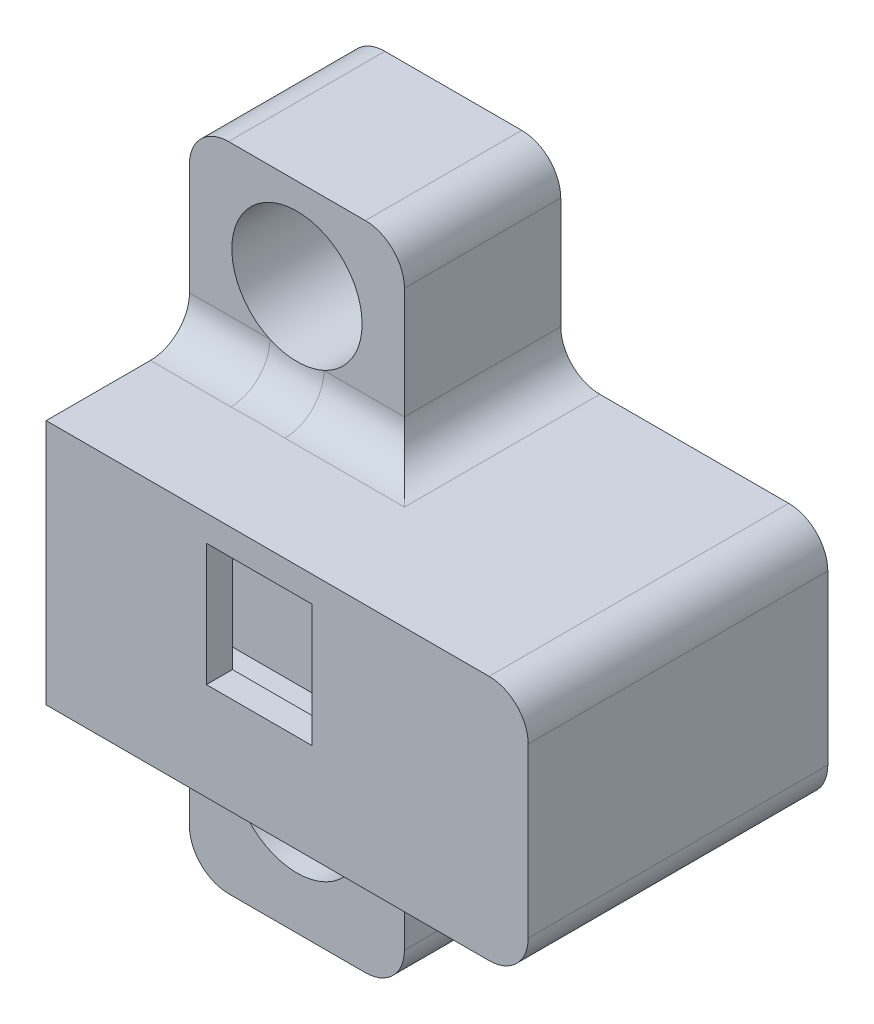
SolidWorks part; units mm, degrees
ref_plane "Alzado" through (0, 0, 0) normal (0, 0, 1) x (1, 0, 0)
ref_plane "Planta" through (0, 0, 0) normal (0, 1, 0) x (1, 0, 0)
ref_plane "Vista lateral" through (0, 0, 0) normal (1, 0, 0) x (0, 0, -1)
sketch "Croquis1" plane through (0, 0, 0) normal (0, 0, 1) x (1, 0, 0)
  line L1 (0, 0) -> (37, 0)
  line L2 (0, 0) -> (0, 18.9)
  line L3 (0, 18.9) -> (37, 18.9)
  line L4 (37, 0) -> (37, 18.9)
  dimension "D1" = 18.9
  dimension "D2" = 37
extrude "Saliente-Extruir1" add sketch "Croquis1" along normal blind 9
shell "Vaciado1" thickness 2
sketch "Croquis2" plane through (0, 0, 0) normal (-1, 0, 0) x (0, 0, 1)
  line L0 (9, 18.9) -> (9, 0) construction
  line L1 (15.4, 3.3) -> (2.6, 3.3)
  line L2 (15.4, 3.3) -> (15.4, 15.6)
  line L3 (15.4, 15.6) -> (2.6, 15.6)
  line L4 (2.6, 3.3) -> (2.6, 15.6)
  line L5 (9, 15.6) -> (9, 3.3) construction
  line L6 (15.4, 9.45) -> (2.6, 9.45) construction
  line L7 (0, 18.9) -> (0, 0) construction
  point P0 (9, 9.45)
  dimension "D1" = 2.6
  dimension "D2" = 12.3
extrude "Cortar-Extruir1" cut sketch "Croquis2" against normal blind 9
sketch "Croquis3" plane through (0, 0, 0) normal (0, 0, -1) x (-1, 0, 0)
  line L0 (-16.5, -16.55) -> (0, -16.55)
  line L1 (-37, 18.9) -> (-16.5, 18.9)
  line L2 (-37, 18.9) -> (-37, 0)
  line L3 (-37, 0) -> (-16.5, 0)
  line L4 (0, 18.9) -> (0, 0)
  line L5 (-16.5, -16.55) -> (-16.5, 0)
  line L6 (0, -16.55) -> (0, 33.45)
  line L7 (-16.5, 33.45) -> (0, 33.45)
  line L8 (-8.25, 33.45) -> (-8.25, -16.55) construction
  line L9 (0, 0) -> (-37, 0) construction
  line L10 (-37, 9.45) -> (0, 9.45) construction
  line L11 (-16.5, 18.9) -> (-16.5, 33.45)
  line L12 (-11.0385, 16.9) -> (-16.5, 33.45) construction
  line L14 (-8.25, 8.45) -> (-5.4615, 16.9) construction
  circle A0 centre (-8.25, 26.45) radius 2.5
  circle A1 centre (-8.25, -7.55) radius 2.5
  point P7 (-8.25, 9.45)
  line M10 (0, 0) -> (0, 18.9)
  line M11 (0, 18.9) -> (-37, 18.9)
  line M12 (-37, 18.9) -> (-37, 0)
  line M13 (-37, 0) -> (0, 0)
  dimension "D3" = 5
  dimension "D1" = 16.5
  dimension "D2" = 50
  dimension "D4" = 7
  dimension "D5" = 0
extrude "Saliente-Extruir2" add sketch "Croquis3" along normal blind 12 contours L11 L6 L7 M11 | L0 L6 L5 M13 | M13 M10 M11 M12
sketch "Croquis4" plane through (0, 0, 0) normal (0, 0, 1) x (1, 0, 0)
  circle A0 centre (8.25, -7.55) radius 5
  circle A1 centre (8.25, 26.45) radius 5
  dimension "D1" = 10
  dimension "D2" = 10
extrude "Cortar-Extruir2" cut sketch "Croquis4" against normal blind 9
fillet "Redondeo1" radius 3 8 edges at (0, 33.45, -6) (16.5, 33.45, -6) (16.5, 18.9, -6) (37, 18.9, -1.5) (37, 0, -1.5) (0, -16.55, -6) (16.5, -16.55, -6) (16.5, 0, -6)
sketch "Croquis5" plane through (0, 0, 2) normal (0, 0, 1) x (1, 0, 0)
  line L0 (2, 9.45) -> (27, 9.45) construction
  line L1 (2, 16.9) -> (2, 2) construction
  line L3 (35, 4.45) -> (27, 4.45)
  line L4 (35, 4.45) -> (35, 14.45)
  line L5 (35, 14.45) -> (27, 14.45)
  line L6 (27, 4.45) -> (27, 14.45)
  line L7 (31, 14.45) -> (31, 4.45) construction
  line L8 (35, 9.45) -> (27, 9.45) construction
  point P4 (31, 9.45)
  dimension "D1" = 10
  dimension "25" = 25
  dimension "D2" = 8
extrude "Cortar-Extruir3" cut sketch "Croquis5" against normal through all and the other way through all
sketch "Croquis6" plane through (0, 0, 9) normal (0, 0, 1) x (1, 0, 0)
sketch "Croquis7" plane through (0, 0, 9) normal (0, 0, 1) x (1, 0, 0)
  line L0 (0, 0) -> (19.5, 0) construction
  line L1 (0, 18.9) -> (12.3, 18.9)
  line L2 (0, 18.9) -> (0, 0)
  line L3 (0, 0) -> (12.3, 0)
  line L4 (12.3, 18.9) -> (12.3, 7.5)
  line L8 (12.3, 7.5) -> (20.5141, 7.5)
  line L9 (20.5141, 2) -> (20.5141, 7.5)
  line L10 (12.3, 0) -> (20.5141, 0)
  line L11 (0, 0) -> (34, 0) construction
  line L12 (20.5141, 0) -> (20.5141, 2)
  dimension "D1" = 12.3
  dimension "D2" = 5.5
extrude "Saliente-Extruir3" add sketch "Croquis7" along normal blind 2
sketch "Croquis8" plane through (0, 0, 9) normal (0, 0, 1) x (1, 0, 0)
  line L0 (20.5141, 2) -> (20.5141, 0) construction
  line L1 (20.5141, 0) -> (34, 0) construction
  line L2 (37, 3) -> (37, 15.9) construction
  line L5 (35, 2) -> (20.5141, 2) construction
  line L6 (12.3, 18.9) -> (12.3, 16.9) construction
  line L7 (12.3, 16.9) -> (35, 16.9) construction
  line L10 (37, 3) -> (37, 15.9) construction
  line L11 (34, 18.9) -> (12.3, 18.9) construction
  line L12 (20.5141, 2) -> (20.5141, 0)
  line L13 (20.5141, 0) -> (34, 0)
  line L14 (37, 3) -> (37, 15.9)
  line L17 (20.3891, 2) -> (20.5141, 2)
  line L18 (12.3, 18.9) -> (12.3, 16.9)
  line L19 (12.3, 16.9) -> (20.3891, 16.9)
  line L22 (37, 3) -> (37, 15.9)
  line L23 (34, 18.9) -> (12.3, 18.9)
  line L24 (20.3891, 16.9) -> (20.3891, 2)
  line L25 (37, 3) -> (37, 15.9)
  line L34 (12.3, 18.9) -> (12.3, 16.9)
  line L35 (12.3, 16.9) -> (35, 16.9)
  line L36 (35, 16.9) -> (35, 2)
  line L37 (35, 2) -> (20.5141, 2)
  line L38 (20.5141, 2) -> (20.5141, 0)
  line L39 (20.5141, 0) -> (34, 0)
  line L40 (37, 3) -> (37, 15.9)
  line L41 (34, 18.9) -> (12.3, 18.9)
  line L42 (12.3, 18.9) -> (12.3, 16.9)
  line L43 (12.3, 16.9) -> (20.3891, 16.9)
  line L45 (20.3891, 2) -> (20.5141, 2)
  line L46 (20.5141, 2) -> (20.5141, 0)
  line L47 (20.5141, 0) -> (34, 0)
  line L48 (37, 3) -> (37, 15.9)
  line L49 (34, 18.9) -> (12.3, 18.9)
  arc A0 (34, 0) -> (37, 3) centre (34, 3) ccw construction
  arc A1 (37, 15.9) -> (34, 18.9) centre (34, 15.9) ccw construction
  arc A2 (34, 0) -> (37, 3) centre (34, 3) ccw
  arc A3 (37, 15.9) -> (34, 18.9) centre (34, 15.9) ccw
  arc A6 (34, 0) -> (37, 3) centre (34, 3) ccw
  arc A7 (37, 15.9) -> (34, 18.9) centre (34, 15.9) ccw
  arc A8 (34, 0) -> (37, 3) centre (34, 3) ccw
  arc A9 (37, 15.9) -> (34, 18.9) centre (34, 15.9) ccw
  line M13 (12.3, 18.9) -> (12.3, 16.9)
  line M14 (12.3, 16.9) -> (35, 16.9)
  line M15 (35, 16.9) -> (35, 2)
  line M17 (37, 3) -> (37, 15.9)
  arc M18 (37, 15.9) -> (34, 18.9) centre (34, 15.9) ccw
  line M19 (34, 18.9) -> (12.3, 18.9)
  line M20 (35, 2) -> (20.5141, 2)
  line M21 (20.5141, 2) -> (20.5141, 0)
  line M22 (20.5141, 0) -> (34, 0)
  arc M23 (34, 0) -> (37, 3) centre (34, 3) ccw
  dimension "D1" = 0
extrude "Saliente-Extruir4" add sketch "Croquis8" along normal blind 2 contours M19 M13 M14 M15 M20 M21 M22 M23 M17 M18 | L24 M14 M20 M15
fillet "Redondeo2" radius 3 2 edges at (9.75, 18.9, 0) (9.75, 0, 0)
